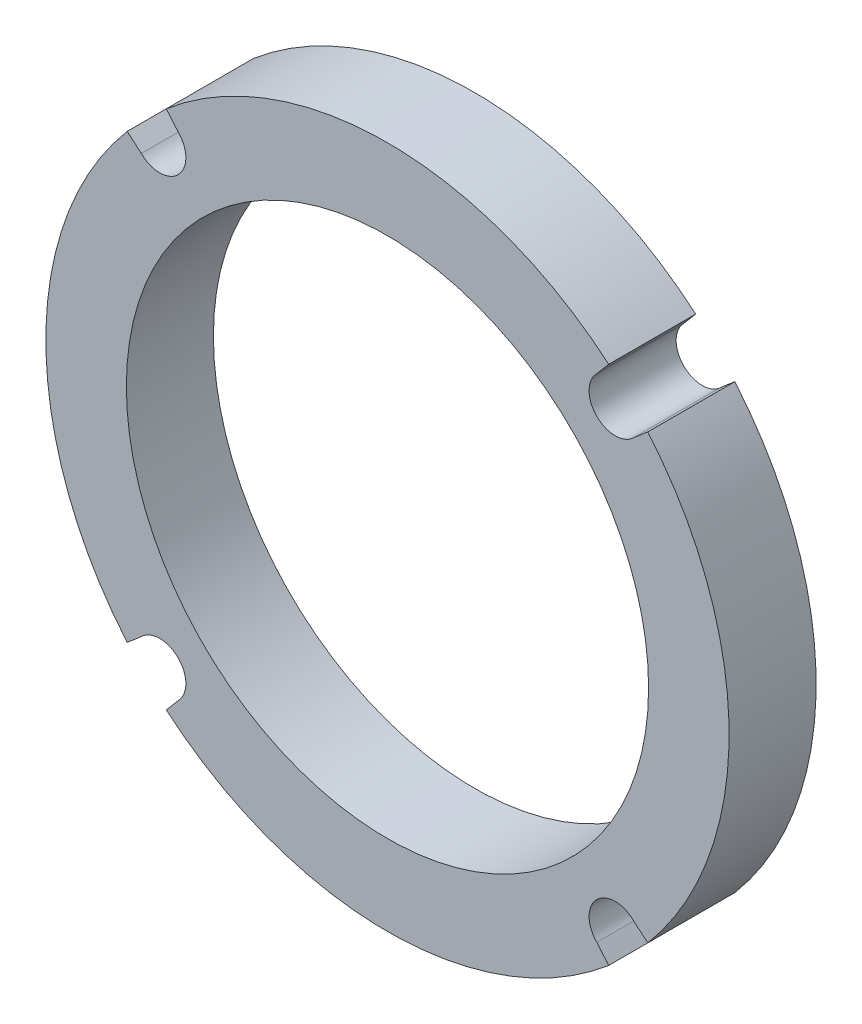
SolidWorks part; units mm, degrees
ref_plane "前视基准面" through (0, 0, 0) normal (0, 0, 1) x (1, 0, 0)
ref_plane "上视基准面" through (0, 0, 0) normal (0, 1, 0) x (1, 0, 0)
ref_plane "右视基准面" through (0, 0, 0) normal (1, 0, 0) x (0, 0, -1)
sketch "草图1" plane through (0, 0, 0) normal (0, 0, 1) x (1, 0, 0)
  line L0 (-26.163, 26.163) -> (-24.0416, 28.2843) construction
  line L1 (26.163, -26.163) -> (-26.163, -26.163) construction
  line L2 (26.163, -26.163) -> (26.163, 26.163) construction
  line L3 (26.163, 26.163) -> (-26.163, 26.163) construction
  line L4 (-26.163, -26.163) -> (-26.163, 26.163) construction
  line L5 (26.163, -26.163) -> (-26.163, 26.163) construction
  line L6 (26.163, 26.163) -> (-26.163, -26.163) construction
  line L7 (-24.0416, 28.2843) -> (-25.4202, 29.9061)
  line L8 (-28.2843, 24.0416) -> (-29.9061, 25.4202)
  line L9 (28.2843, 24.0416) -> (29.9061, 25.4202)
  line L10 (24.0416, 28.2843) -> (25.4202, 29.9061)
  line L11 (24.0416, -28.2843) -> (25.4202, -29.9061)
  line L12 (28.2843, -24.0416) -> (29.9061, -25.4202)
  line L13 (-28.2843, -24.0416) -> (-29.9061, -25.4202)
  line L14 (-24.0416, -28.2843) -> (-25.4202, -29.9061)
  arc A4 (-29.9061, 25.4202) -> (-29.9061, -25.4202) centre (0, 0) ccw
  arc A5 (-28.2843, 24.0416) -> (-24.0416, 28.2843) centre (-26.163, 26.163) ccw
  arc A6 (24.0416, 28.2843) -> (28.2843, 24.0416) centre (26.163, 26.163) ccw
  arc A7 (-24.0416, -28.2843) -> (-28.2843, -24.0416) centre (-26.163, -26.163) ccw
  arc A8 (28.2843, -24.0416) -> (24.0416, -28.2843) centre (26.163, -26.163) ccw
  arc A9 (25.4202, 29.9061) -> (-25.4202, 29.9061) centre (0, 0) ccw
  arc A10 (29.9061, -25.4202) -> (29.9061, 25.4202) centre (0, 0) ccw
  arc A11 (-25.4202, -29.9061) -> (25.4202, -29.9061) centre (0, 0) ccw
  point P0 (0, 0)
  point P32 (0, 0)
  dimension "D2" = 45
  dimension "D6" = 78.5
  dimension "D7" = 6
  dimension "D8" = 6
  dimension "D9" = 6
  dimension "D10" = 6
  dimension "D1" = 37
extrude "凸台-拉伸1" add sketch "草图1" along normal blind 10
sketch "草图2" plane through (0, 0, 0) normal (0, 0, -1) x (-1, 0, 0)
  circle A0 centre (0, 0) radius 30
  dimension "D1" = 60
extrude "切除-拉伸1" cut sketch "草图2" against normal blind 10
